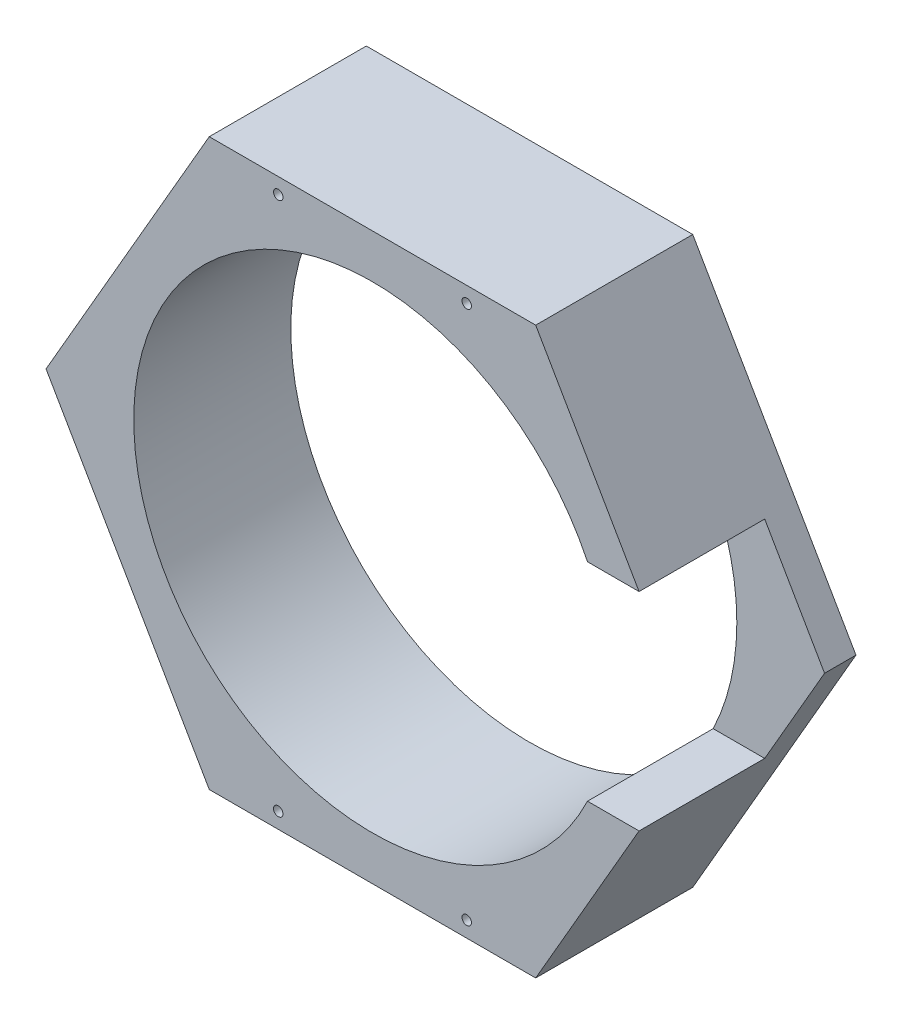
SolidWorks part; units mm, degrees
ref_plane "Front Plane" through (0, 0, 0) normal (0, 0, 1) x (1, 0, 0)
ref_plane "Top Plane" through (0, 0, 0) normal (0, 1, 0) x (1, 0, 0)
ref_plane "Right Plane" through (0, 0, 0) normal (1, 0, 0) x (0, 0, -1)
sketch "Sketch1" plane through (0, 0, 0) normal (0, 0, 1) x (1, 0, 0)
  line L1 (103.923, 0) -> (51.9615, 90)
  line L2 (51.9615, 90) -> (-51.9615, 90)
  line L3 (-51.9615, 90) -> (-103.923, 0)
  line L4 (-103.923, 0) -> (-51.9615, -90)
  line L5 (-51.9615, -90) -> (51.9615, -90)
  line L6 (51.9615, -90) -> (103.923, 0)
  arc A0 (-31.357, 84.3608) -> (-31.357, -84.3608) centre (0, 0) ccw construction
  circle A1 centre (0, 0) radius 76
  circle A2 centre (30, -85) radius 1.5
  circle A3 centre (-30, -85) radius 1.5
  circle A4 centre (30, 85) radius 1.5
  circle A5 centre (-30, 85) radius 1.5
  arc A6 (28.5424, 85.3542) -> (-28.5424, 85.3542) centre (0, 0) ccw construction
  arc A7 (31.357, -84.3608) -> (31.357, 84.3608) centre (0, 0) ccw construction
  arc A8 (-28.5424, -85.3542) -> (28.5424, -85.3542) centre (0, 0) ccw construction
  dimension "D2" = 152
  dimension "D9" = 3
  dimension "D10" = 3
  dimension "D11" = 3
  dimension "D12" = 3
  dimension "D1" = 180
extrude "Boss-Extrude1" add sketch "Sketch1" along normal blind 50
sketch "Sketch4" plane through (0, 0, 50) normal (0, 0, 1) x (1, 0, 0)
  line L0 (63.923, 0) -> (63.923, 33)
  line L1 (63.923, 0) -> (63.923, -33)
  line L2 (103.923, 0) -> (63.923, 0)
  line L3 (63.923, 33) -> (103.923, 33)
  line L4 (63.923, -33) -> (103.923, -33)
  line L5 (103.923, -33) -> (103.923, 33)
  line M3 (51.9615, -90) -> (103.923, 0)
  line M4 (103.923, 0) -> (51.9615, 90)
  circle M9 centre (0, 0) radius 76
  dimension "D2" = 33
  dimension "D1" = 40
  dimension "D3" = 33
  dimension "D4" = 40
  dimension "D5" = 40
extrude "Cut-Extrude1" cut sketch "Sketch4" against normal blind 40 contours L3 L2 M9 M4 | L4 L2 M9 M3
